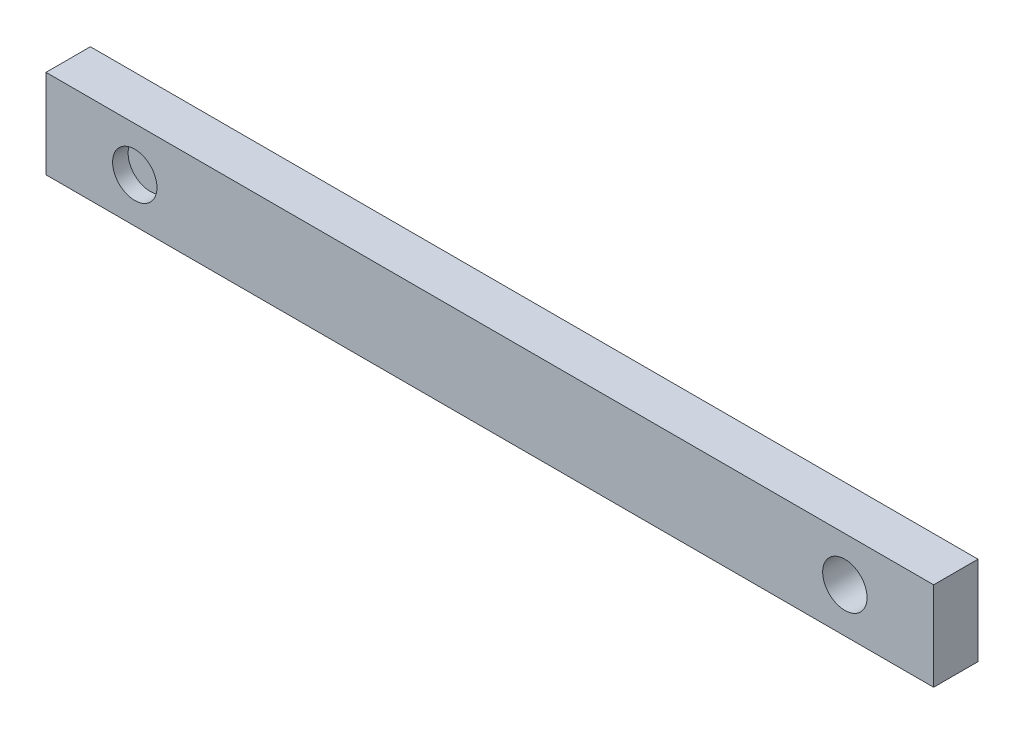
SolidWorks part; units mm, degrees
ref_plane "Front Plane" through (0, 0, 0) normal (0, 0, 1) x (1, 0, 0)
ref_plane "Top Plane" through (0, 0, 0) normal (0, 1, 0) x (1, 0, 0)
ref_plane "Right Plane" through (0, 0, 0) normal (1, 0, 0) x (0, 0, -1)
sketch "Sketch1" plane through (0, 0, 0) normal (0, 0, 1) x (1, 0, 0)
  line L0 (-190.9098, 0) -> (211.8535, 0) construction
  line L1 (0, 94.3809) -> (0, -93.3068) construction
sketch "Sketch2" plane through (0, 0, 0) normal (0, 0, 1) x (1, 0, 0)
  line L0 (-190.9098, 0) -> (211.8535, 0) construction
  line L1 (-97.8357, -10) -> (102.1643, -10)
  line L2 (-97.8357, -10) -> (-97.8357, 10)
  line L3 (-97.8357, 10) -> (102.1643, 10)
  line L4 (102.1643, -10) -> (102.1643, 10)
  circle A0 centre (82.1643, 0) radius 5
  point P0 (0, 0)
  dimension "D3" = 10
  dimension "D1" = 200
  dimension "D2" = 20
  dimension "D4" = 20
extrude "Boss-Extrude2" add sketch "Sketch2" along normal blind 10
sketch "Sketch3" plane through (0, 0, 10) normal (0, 0, 1) x (1, 0, 0)
  line L0 (-190.9098, 0) -> (211.8535, 0) construction
  line L1 (-97.8357, 10) -> (-97.8357, -10) construction
  circle A0 centre (-77.8357, 0) radius 5
  dimension "D1" = 10
  dimension "D2" = 20
extrude "Cut-Extrude1" cut sketch "Sketch3" against normal blind 3.5
